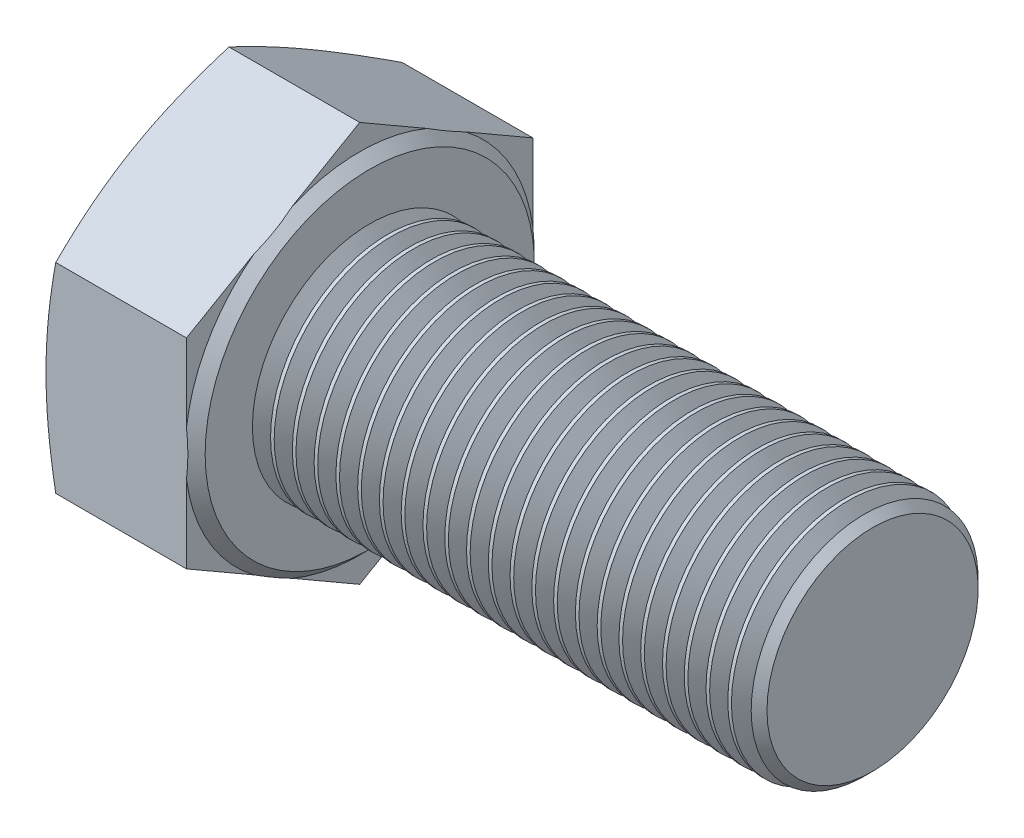
SolidWorks part; units mm, degrees
ref_plane "Front" through (0, 0, 0) normal (0, 0, 1) x (1, 0, 0)
ref_plane "Top" through (0, 0, 0) normal (0, 1, 0) x (1, 0, 0)
ref_plane "Right" through (0, 0, 0) normal (1, 0, 0) x (0, 0, -1)
other "Configuration Table"
sketch "Sketch2" plane through (0, 0, 0) normal (1, 0, 0) x (0, 0, -1)
  line L1 (10.335, -5.9669) -> (10.335, 5.9669)
  line L2 (10.335, 5.9669) -> (0, 11.9338)
  line L3 (0, 11.9338) -> (-10.335, 5.9669)
  line L4 (-10.335, 5.9669) -> (-10.335, -5.9669)
  line L5 (-10.335, -5.9669) -> (0, -11.9338)
  line L6 (0, -11.9338) -> (10.335, -5.9669)
  circle A0 centre (0, 0) radius 10.335 construction
  dimension "s" = 20.67
extrude "BaseHead" add sketch "Sketch2" along normal blind 8.98
sketch "Sketch3" plane through (0, 0, 0) normal (0, 0, 1) x (1, 0, 0)
  line L0 (8.98, 11.9338) -> (8.98, 9.82)
  line L2 (8.98, 9.82) -> (8.38, 10.42)
  line L3 (8.38, 10.42) -> (8.38, 11.9338)
  line L5 (8.38, 11.9338) -> (8.98, 11.9338)
  line L6 (-0.9571, 0) -> (7.6478, 0) construction
  line L7 (8.98, 11.9338) -> (0, 11.9338) construction
  dimension "D1" = 45
  dimension "c" = 0.6
  dimension "Dw" = 19.64
revolve "BearingFace" cut sketch "Sketch3" angle 360 about L6
sketch "Sketch4" plane through (0, 0, 0) normal (0, 0, 1) x (1, 0, 0)
  line L0 (-0.4935, 0) -> (3.5626, 0) construction
  line L2 (0, 11.9338) -> (0.5819, 11.9338)
  line L4 (0.5819, 11.9338) -> (0, 10.335)
  line L6 (0, 10.335) -> (0, 11.9338)
  line L7 (8.38, 11.9338) -> (0, 11.9338) construction
  dimension "D1" = 20
  dimension "D2" = 20.67
revolve "HeadChamfer" cut sketch "Sketch4" angle 360 about L0
sketch "Sketch5" plane through (8.98, 0, 0) normal (1, 0, 0) x (0, 0, -1)
  circle A0 centre (0, 0) radius 7
  dimension "d" = 14
extrude "BaseBody" add sketch "Sketch5" along normal blind 30
cosmetic thread "ThreadCosmetic1" [suppressed] parameters "D2"=11.835
chamfer "Chamfer1" distance 0.7 angle 45 1 edges at (38.98, 0, -7)
fillet "HeadFillet" [suppressed] radius 0.6
sketch "Sketch6" plane through (0, 0, 0) normal (0, 0, 1) x (1, 0, 0)
  line L0 (8.98, 8.0825) -> (10.0625, 8.0825)
  line L1 (10.0625, 8.0825) -> (10.0625, 7)
  line L2 (10.0625, 7) -> (9.5213, 6.0625)
  line L3 (9.5213, 6.0625) -> (8.98, 7)
  line L4 (8.98, 7) -> (8.98, 8.0825)
  line L5 (38.28, 7) -> (8.98, 7) construction
  line L6 (8.98, -9.82) -> (8.98, 9.82) construction
  dimension "D1" = 1.0825
revolve "Cut-Revolve10" cut sketch "Sketch6" angle 360 about axis through (-0.9571, 0, 0) along (1, 0, 0)
pattern_linear "LPattern10" count 23 spacing 1.299 along (1, 0, 0) of "Cut-Revolve10"
equation "\"D2@Sketch4\" = \"s@Sketch2\""
equation "\"D1@Chamfer1\" = 0.05 * \"d@Sketch5\""
equation "\"D1@Sketch6\" =  ( \"d@Sketch5\" - \"D2@ThreadCosmetic1\" )  / 2"
equation "\"pitch@LPattern10\" = \"D1@Sketch6\" * 1.2"
equation "\"D1@LPattern10\" = \"l@BaseBody\" / \"pitch@LPattern10\""
